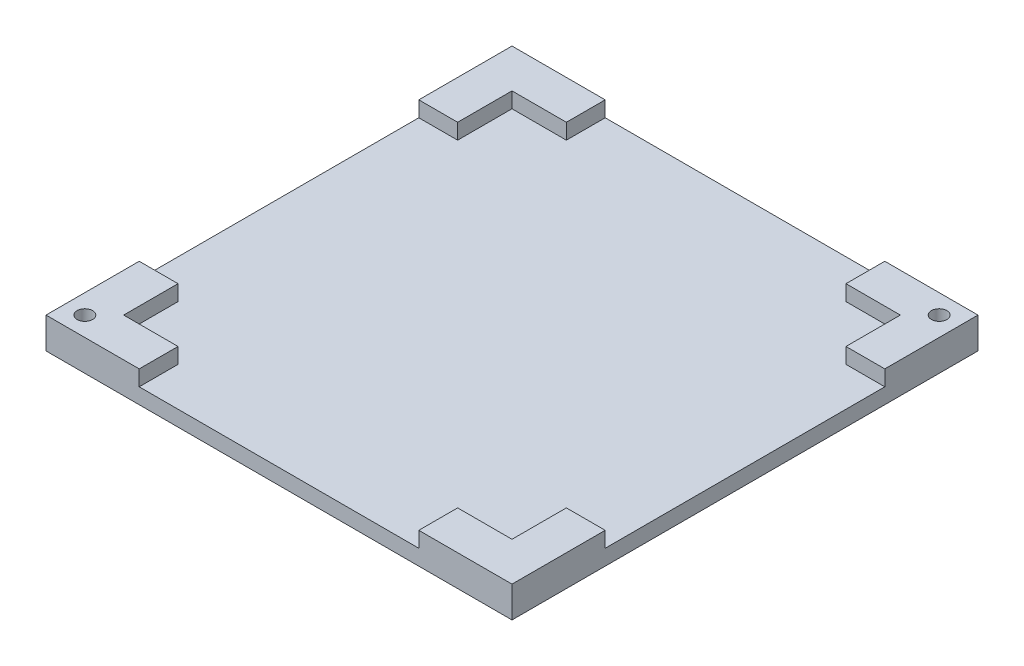
SolidWorks part; units mm, degrees
material "6061 Alloy"
ref_plane "Front Plane" through (0, 0, 0) normal (0, 0, 1) x (1, 0, 0)
ref_plane "Top Plane" through (0, 0, 0) normal (0, 1, 0) x (1, 0, 0)
ref_plane "Right Plane" through (0, 0, 0) normal (1, 0, 0) x (0, 0, -1)
sketch "Sketch1" plane through (0, 0, 0) normal (0, 1, 0) x (1, 0, 0)
  line L1 (-150, -150) -> (150, -150)
  line L2 (-150, -150) -> (-150, 150)
  line L3 (-150, 150) -> (150, 150)
  line L4 (150, -150) -> (150, 150)
  line L5 (-150, -150) -> (150, 150) construction
  line L6 (-150, 150) -> (150, -150) construction
  point P0 (0, 0)
  dimension "D1" = 300
  dimension "D2" = 300
extrude "Boss-Extrude1" add sketch "Sketch1" along normal blind 10
sketch "Sketch2" plane through (0, 10, 0) normal (0, 1, 0) x (1, 0, 0)
  line L0 (150, 150) -> (90, 150)
  line L9 (150, 150) -> (-150, 150) construction
  line L10 (90, 150) -> (90, 125)
  line L11 (90, 125) -> (125, 125)
  line L12 (125, 125) -> (125, 90)
  line L13 (125, 90) -> (150, 90)
  line L14 (150, -150) -> (150, 150) construction
  line L15 (150, 90) -> (150, 150)
  line L16 (0, 0) -> (0, 150) construction
  line L17 (0, 0) -> (150, 0) construction
  line L18 (-150, 90) -> (-150, 150)
  line L19 (-125, 90) -> (-150, 90)
  line L20 (-125, 125) -> (-125, 90)
  line L21 (-90, 125) -> (-125, 125)
  line L22 (-90, 150) -> (-90, 125)
  line L23 (-150, 150) -> (-90, 150)
  line L24 (-150, -150) -> (-90, -150)
  line L25 (-90, -150) -> (-90, -125)
  line L26 (-90, -125) -> (-125, -125)
  line L27 (-125, -125) -> (-125, -90)
  line L28 (-125, -90) -> (-150, -90)
  line L29 (-150, -90) -> (-150, -150)
  line L30 (150, -90) -> (150, -150)
  line L31 (125, -90) -> (150, -90)
  line L32 (125, -125) -> (125, -90)
  line L33 (90, -125) -> (125, -125)
  line L34 (90, -150) -> (90, -125)
  line L35 (150, -150) -> (90, -150)
  dimension "D3" = 60
  dimension "D4" = 25
  dimension "D5" = 25
  dimension "D6" = 60
extrude "Boss-Extrude2" add sketch "Sketch2" along normal blind 10
sketch "Sketch3" plane through (0, 20, 0) normal (0, 1, 0) x (1, 0, 0)
  line L0 (-125, -137.5) -> (-150, -137.5) construction
  line L3 (150, 137.5) -> (125, 137.5) construction
  line L6 (-125, -125) -> (-125, -150) construction
  line L7 (-90, -125) -> (-125, -125) construction
  line L8 (-90, -125) -> (-125, -125) construction
  line L9 (-150, -150) -> (-90, -150) construction
  line L10 (-150, -90) -> (-150, -150) construction
  line L11 (150, 90) -> (150, 150) construction
  line L12 (125, 125) -> (125, 150) construction
  line L13 (150, 150) -> (90, 150) construction
  circle A0 centre (-137.5, -137.5) radius 5
  circle A1 centre (137.5, 137.5) radius 5
  dimension "D1" = 10
extrude "Cut-Extrude1" cut sketch "Sketch3" against normal blind 15
